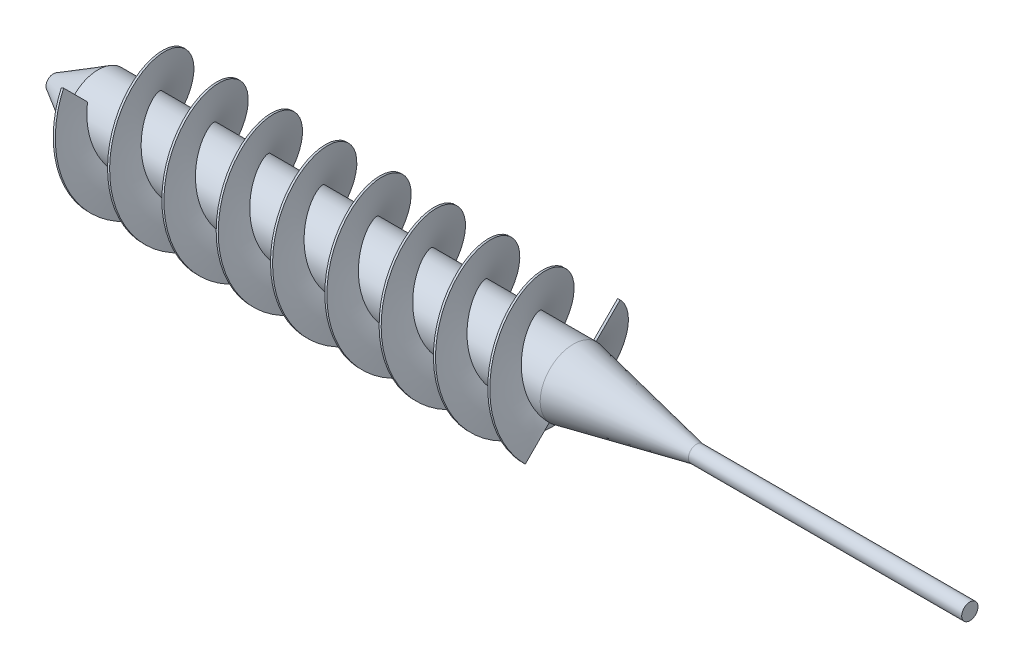
SolidWorks part; units mm, degrees
ref_plane "Front Plane" through (0, 0, 0) normal (0, 0, 1) x (1, 0, 0)
ref_plane "Top Plane" through (0, 0, 0) normal (0, 1, 0) x (1, 0, 0)
ref_plane "Right Plane" through (0, 0, 0) normal (1, 0, 0) x (0, 0, -1)
sketch "Sketch1" plane through (0, 0, 0) normal (0, 0, 1) x (1, 0, 0)
  line L0 (0, 0) -> (-1350, 0)
  line L1 (-1350, 0) -> (-1350, 10.7994)
  line L2 (-1350, 10.7994) -> (-1284.1179, 48.7994)
  line L3 (-1284.1179, 48.7994) -> (-584.1179, 48.7994)
  line L4 (-584.1179, 48.7994) -> (-402.5867, 12)
  line L5 (-402.5867, 12) -> (0, 12)
  line L6 (0, 12) -> (0, 0)
  dimension "D1" = 12
  dimension "D2" = 1350
revolve "Revolve3" add sketch "Sketch1" angle 360 about L0
ref_plane "Plane1" through (-1265, 0, 0) normal (-1, 0, 0) x (0, 0, 1)
sketch "Sketch3" plane through (-1265, 0, 0) normal (-1, 0, 0) x (0, 0, 1)
  circle A0 centre (0, 0) radius 50
curve "Helix/Spiral1" pitch 160 height 680 turns 4.25
ref_plane "Plane2" through (-585, -35.3553, 35.3553) normal (0.4538, -0.6301, -0.6301) x (-0.8911, -0.3209, -0.3209)
sketch "Sketch4" plane through (-585, -35.3553, 35.3553) normal (0.4538, -0.6301, -0.6301) x (-0.8911, -0.3209, -0.3209)
  line L0 (-0.7861, 1.2006) -> (622.9764, 1.2006) construction
  line L1 (-0.0018, 1.2006) -> (2.9982, 1.2006)
  line L2 (-0.0018, 1.2006) -> (-0.0018, -48.7994)
  line L3 (-0.0018, -48.7994) -> (2.9982, -48.7994)
  line L4 (2.9982, 1.2006) -> (2.9982, -48.7994)
  dimension "D1" = 3
  dimension "D2" = 50
sweep "Sweep1" add profiles "Sketch4" path "Helix/Spiral1"
pattern_circular "CirPattern1" count 2 over 360 about axis through (0, 0, 0) along (1, 0, 0) of bodies 104
